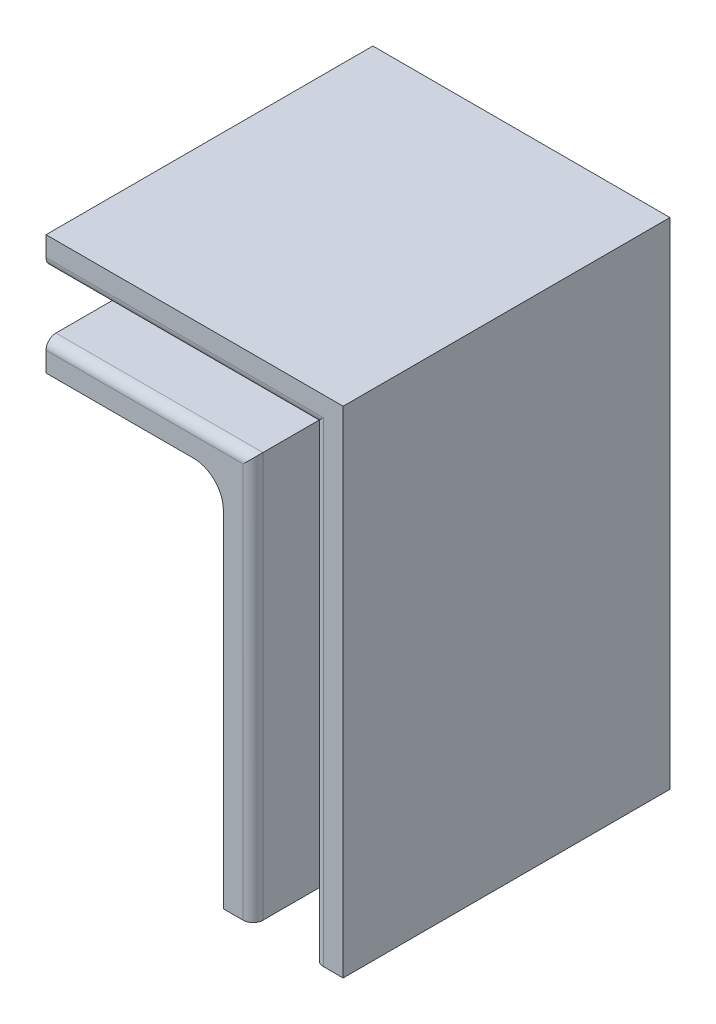
SolidWorks part; units mm, degrees
ref_plane "Front" through (0, 0, 0) normal (0, 0, 1) x (1, 0, 0)
ref_plane "Top" through (0, 0, 0) normal (0, 1, 0) x (1, 0, 0)
ref_plane "Right" through (0, 0, 0) normal (1, 0, 0) x (0, 0, -1)
sketch "Sketch1" plane through (0, 0, 0) normal (0, 0, 1) x (1, 0, 0)
  line L5 (0, 0) -> (30, 0)
  line L6 (0, 0) -> (0, 50)
  line L7 (0, 50) -> (30, 50)
  line L8 (30, 0) -> (30, 50)
  dimension "D1" = 50
  dimension "D2" = 30
extrude "Boss-Extrude1" add sketch "Sketch1" along normal blind 3
sketch "Sketch2" plane through (0, 0, 3) normal (0, 0, 1) x (1, 0, 0)
  line L39 (0, 50) -> (30, 50)
  line L44 (30, 50) -> (30, 0)
  line L45 (30, 0) -> (27, 0)
  line L46 (0, 0) -> (30, 0) construction
  line L47 (27, 0) -> (27, 47)
  line L48 (27, 47) -> (0, 47)
  line L49 (0, 50) -> (0, 0) construction
  line L50 (0, 47) -> (0, 50)
  line L51 (0, 40.9) -> (20.9, 40.9)
  line L52 (20.9, 40.9) -> (20.9, 0)
  line L53 (20.9, 0) -> (17.9, 0)
  line L54 (17.9, 0) -> (17.9, 37.9)
  line L55 (17.9, 37.9) -> (0, 37.9)
  line L56 (0, 37.9) -> (0, 40.9)
  dimension "D1" = 3
  dimension "D2" = 6.1
  dimension "D3" = 6.1
extrude "Boss-Extrude2" add sketch "Sketch2" along normal blind 30
fillet "Fillet1" radius 3 7 edges at (20.9, 20.45, 3) (10.45, 40.9, 3) (13.5, 47, 3) (17.9, 37.9, 18) (8.95, 37.9, 3) (17.9, 18.95, 3) (27, 23.5, 3)
fillet "Fillet2" radius 1 4 edges at (10.45, 40.9, 33) (13.5, 47, 33) (27, 23.5, 33) (20.9, 20.45, 33)
